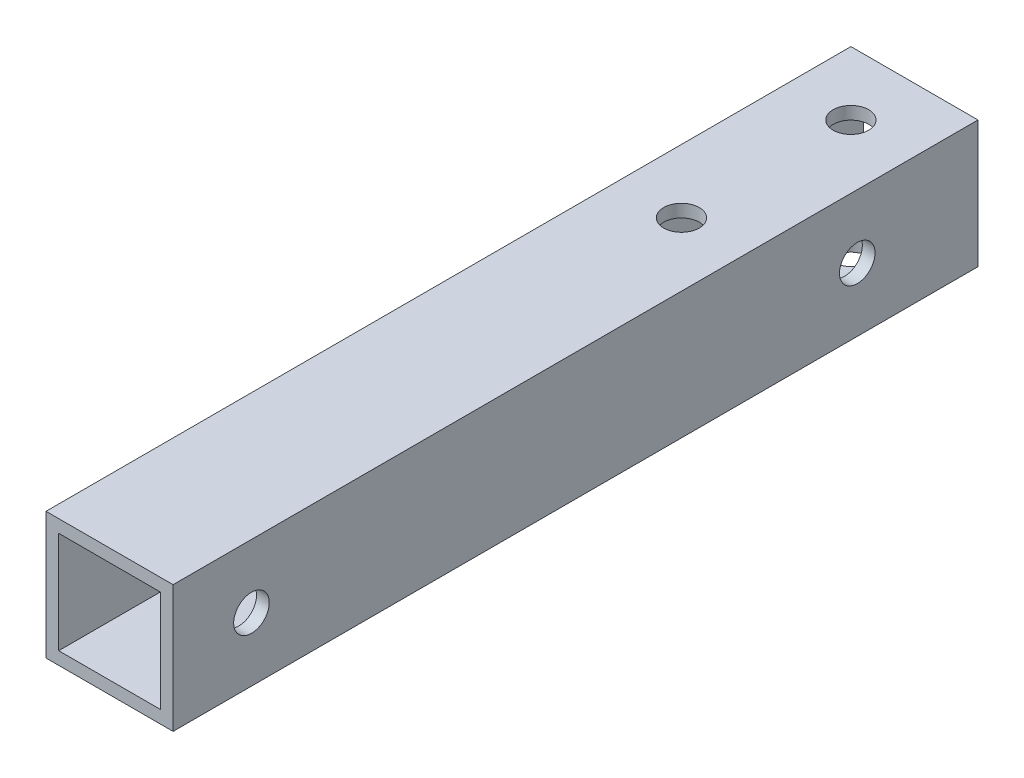
SolidWorks part; units mm, degrees
material "5052-H34"
ref_plane "正面" through (0, 0, 0) normal (0, 0, 1) x (1, 0, 0)
ref_plane "平面" through (0, 0, 0) normal (0, 1, 0) x (1, 0, 0)
ref_plane "右側面" through (0, 0, 0) normal (1, 0, 0) x (0, 0, -1)
sketch "ｽｹｯﾁ1" plane through (0, 0, 0) normal (0, 0, 1) x (1, 0, 0)
  line L1 (-7.5, 7.5) -> (7.5, 7.5)
  line L2 (-7.5, 7.5) -> (-7.5, -7.5)
  line L3 (-7.5, -7.5) -> (7.5, -7.5)
  line L4 (7.5, 7.5) -> (7.5, -7.5)
  line L5 (-7.5, 7.5) -> (7.5, -7.5) construction
  line L6 (-7.5, -7.5) -> (7.5, 7.5) construction
  point P0 (0, 0)
  dimension "D1" = 15
extrude "押し出し-薄板1" add sketch "ｽｹｯﾁ1" along normal blind 95 thin
sketch "ｽｹｯﾁ2" plane through (7.5, 0, 0) normal (1, 0, 0) x (0, 0, -1)
  line L0 (-95, 0) -> (-14.25, 0) construction
  line L1 (-95, -7.5) -> (-95, 7.5) construction
  circle A0 centre (-14.25, 0) radius 2.1
  circle A1 centre (-85.75, 0) radius 2.1
  dimension "D1" = 4.2
  dimension "D2" = 9.25
  dimension "D3" = 71.5
extrude "ｶｯﾄ - 押し出し1" cut sketch "ｽｹｯﾁ2" against normal through all
sketch "ｽｹｯﾁ3" plane through (0, 7.5, 0) normal (0, 1, 0) x (1, 0, 0)
  line L0 (0, 0) -> (0, -27.5) construction
  circle A0 centre (0, -27.5) radius 2.1
  circle A1 centre (0, -7.5) radius 2.1
  dimension "D1" = 4.2
  dimension "D2" = 20
  dimension "D3" = 7.5
extrude "ｶｯﾄ - 押し出し2" cut sketch "ｽｹｯﾁ3" against normal through all
